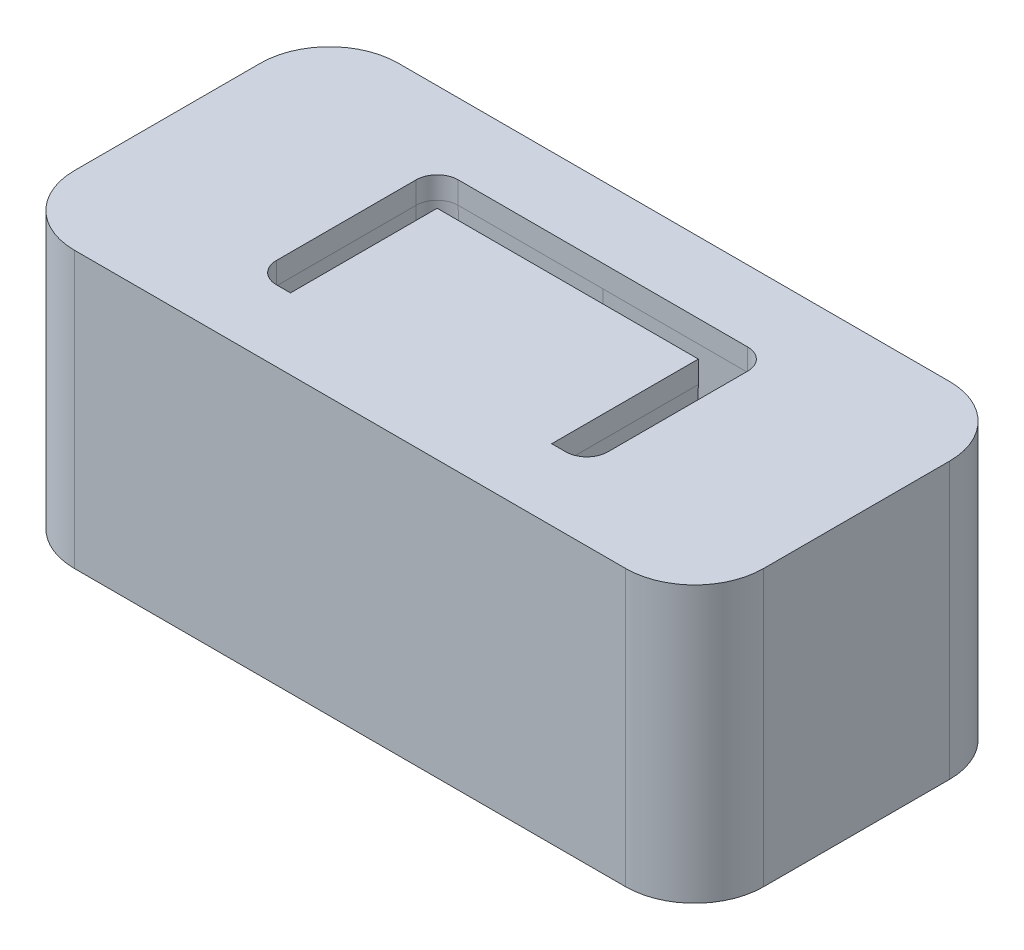
SolidWorks part; units mm, degrees
material "K110"
ref_plane "Front Plane" through (0, 0, 0) normal (0, 0, 1) x (1, 0, 0)
ref_plane "Top Plane" through (0, 0, 0) normal (0, 1, 0) x (1, 0, 0)
ref_plane "Right Plane" through (0, 0, 0) normal (1, 0, 0) x (0, 0, -1)
sketch "Sketch2" plane through (0, 0, 0) normal (0, 1, 0) x (1, 0, 0)
  line L1 (-50, -23.5) -> (50, -23.5)
  line L2 (-50, -23.5) -> (-50, 23.5)
  line L3 (-50, 23.5) -> (50, 23.5)
  line L4 (50, -23.5) -> (50, 23.5)
  line L5 (-50, -23.5) -> (50, 23.5) construction
  line L6 (-50, 23.5) -> (50, -23.5) construction
  point P0 (0, 0)
  dimension "D1" = 100
  dimension "D2" = 47
extrude "Boss-Extrude1" add sketch "Sketch2" against normal blind 40
fillet "Fillet1" radius 10 4 edges at (-50, -20, -23.5) (50, -20, -23.5) (50, -20, 23.5) (-50, -20, 23.5)
sketch "Sketch3" plane through (0, 0, 0) normal (0, 1, 0) x (1, 0, 0)
  line L16 (24.05, -10.14) -> (24.05, 10.14)
  line L17 (18.95, -13.19) -> (21, -13.19)
  line L18 (18.95, 8.09) -> (18.95, -13.19)
  line L19 (-18.95, 8.09) -> (18.95, 8.09)
  line L20 (-18.95, -13.19) -> (-18.95, 8.09)
  line L21 (-21, -13.19) -> (-18.95, -13.19)
  line L22 (-24.05, 10.14) -> (-24.05, -10.14)
  line L23 (21, 13.19) -> (-21, 13.19)
  line L24 (24.05, -10.14) -> (24.05, 10.14)
  line L25 (18.95, -13.19) -> (21, -13.19)
  line L26 (18.95, 8.09) -> (18.95, -13.19)
  line L27 (-18.95, 8.09) -> (18.95, 8.09)
  line L28 (-18.95, -13.19) -> (-18.95, 8.09)
  line L29 (-21, -13.19) -> (-18.95, -13.19)
  line L30 (-24.05, 10.14) -> (-24.05, -10.14)
  line L31 (21, 13.19) -> (-21, 13.19)
  arc A8 (24.05, 10.14) -> (21, 13.19) centre (21, 10.14) ccw
  arc A9 (21, -13.19) -> (24.05, -10.14) centre (21, -10.14) ccw
  arc A10 (-24.05, -10.14) -> (-21, -13.19) centre (-21, -10.14) ccw
  arc A11 (-21, 13.19) -> (-24.05, 10.14) centre (-21, 10.14) ccw
  arc A12 (24.05, 10.14) -> (21, 13.19) centre (21, 10.14) ccw
  arc A13 (21, -13.19) -> (24.05, -10.14) centre (21, -10.14) ccw
  arc A14 (-24.05, -10.14) -> (-21, -13.19) centre (-21, -10.14) ccw
  arc A15 (-21, 13.19) -> (-24.05, 10.14) centre (-21, 10.14) ccw
  dimension "D1" = 0.05
extrude "Cut-Extrude1" cut sketch "Sketch3" against normal up to next
hole_wizard "M6 Tapped Hole1" positions "Sketch6" profile "Sketch5" tap size "M6" standard "ISO"
sketch "Sketch6" plane through (0, -40, 0) normal (0, -1, 0) x (-1, 0, 0)
  line L0 (-50, -13.5) -> (-50, 13.5) construction
  line L1 (-40, 23.5) -> (40, 23.5) construction
  line L2 (40, -23.5) -> (-40, -23.5) construction
  line L3 (50, 13.5) -> (50, -13.5) construction
  point P0 (-43, 16.5)
  point P2 (43, 16.5)
  point P4 (43, -16.5)
  point P6 (-43, -16.5)
  dimension "D1" = 7
  dimension "D2" = 7
  dimension "D3" = 7
  dimension "D4" = 7
sketch "Sketch5" plane through (43, -40, -16.5) normal (1, 0, 0) x (0, 0, -1)
  line L0 (0, 0) -> (0, 18.5022)
  line L1 (0, 18.5022) -> (2.5, 17)
  line L2 (2.5, 17) -> (2.5, 0.525)
  line L3 (2.5, 0.525) -> (3.025, 0)
  line L5 (3.025, 0) -> (0, 0)
  line L6 (-2.5, 0.525) -> (-3.025, 0) construction
  line L10 (0, 18.5022) -> (-2.5, 17) construction
  line L11 (0, -6.35) -> (0, 107.95) construction
  dimension "Tap Drill Dia." = 5
  dimension "Tap Drill Depth" = 17
  dimension "Near C'Sink Dia." = 6.05
  dimension "Near C'Sink Angle" = 90
  dimension "Drill Angle" = 118
cosmetic thread "Hole Thread1" parameters "D1"=12, "D2"=6
cosmetic thread "Hole Thread2" parameters "D1"=12, "D2"=6
cosmetic thread "Hole Thread3" parameters "D1"=12, "D2"=6
cosmetic thread "Hole Thread4" parameters "D1"=12, "D2"=6
sketch "Sketch7" plane through (0, 0, 0) normal (1, 0, 0) x (0, 0, -1)
  line L0 (13.19, -3.2) -> (13.8323, -40)
  line L1 (13.19, -40) -> (13.19, 0) construction
  line L2 (13.5, -40) -> (23.5, -40) construction
  line L3 (13.8323, -40) -> (13.19, -40)
  line L4 (13.19, -40) -> (13.19, -3.2)
  line L5 (23.5, 0) -> (13.5, 0) construction
  dimension "D1" = 3.2
  dimension "D2" = 1
sketch "Sketch8" plane through (0, 0, 0) normal (0, 1, 0) x (1, 0, 0)
  line L0 (18.95, 8.09) -> (18.95, -13.19) construction
  line L1 (-18.95, -13.19) -> (-18.95, 8.09) construction
  line L2 (-18.95, 8.09) -> (18.95, 8.09) construction
  line L3 (-21, -13.19) -> (-18.95, -13.19) construction
  line L4 (-24.05, 10.14) -> (-24.05, -10.14) construction
  line L5 (18.95, -13.19) -> (21, -13.19) construction
  line L6 (24.05, -10.14) -> (24.05, 10.14) construction
  line L7 (21, 13.19) -> (-21, 13.19) construction
  line L8 (18.95, 8.09) -> (18.95, -13.19)
  line L9 (-18.95, -13.19) -> (-18.95, 8.09)
  line L10 (-18.95, 8.09) -> (18.95, 8.09)
  line L11 (-21, -13.19) -> (-18.95, -13.19)
  line L12 (-24.05, 10.14) -> (-24.05, -10.14)
  line L13 (18.95, -13.19) -> (21, -13.19)
  line L14 (24.05, -10.14) -> (24.05, 10.14)
  line L15 (21, 13.19) -> (-21, 13.19)
  arc A0 (-24.05, -10.14) -> (-21, -13.19) centre (-21, -10.14) ccw construction
  arc A1 (-21, 13.19) -> (-24.05, 10.14) centre (-21, 10.14) ccw construction
  arc A2 (21, -13.19) -> (24.05, -10.14) centre (21, -10.14) ccw construction
  arc A3 (24.05, 10.14) -> (21, 13.19) centre (21, 10.14) ccw construction
  arc A4 (-24.05, -10.14) -> (-21, -13.19) centre (-21, -10.14) ccw
  arc A5 (-21, 13.19) -> (-24.05, 10.14) centre (-21, 10.14) ccw
  arc A6 (21, -13.19) -> (24.05, -10.14) centre (21, -10.14) ccw
  arc A7 (24.05, 10.14) -> (21, 13.19) centre (21, 10.14) ccw
sweep "Cut-Sweep1" cut profiles "Sketch7" path "Sketch8"
